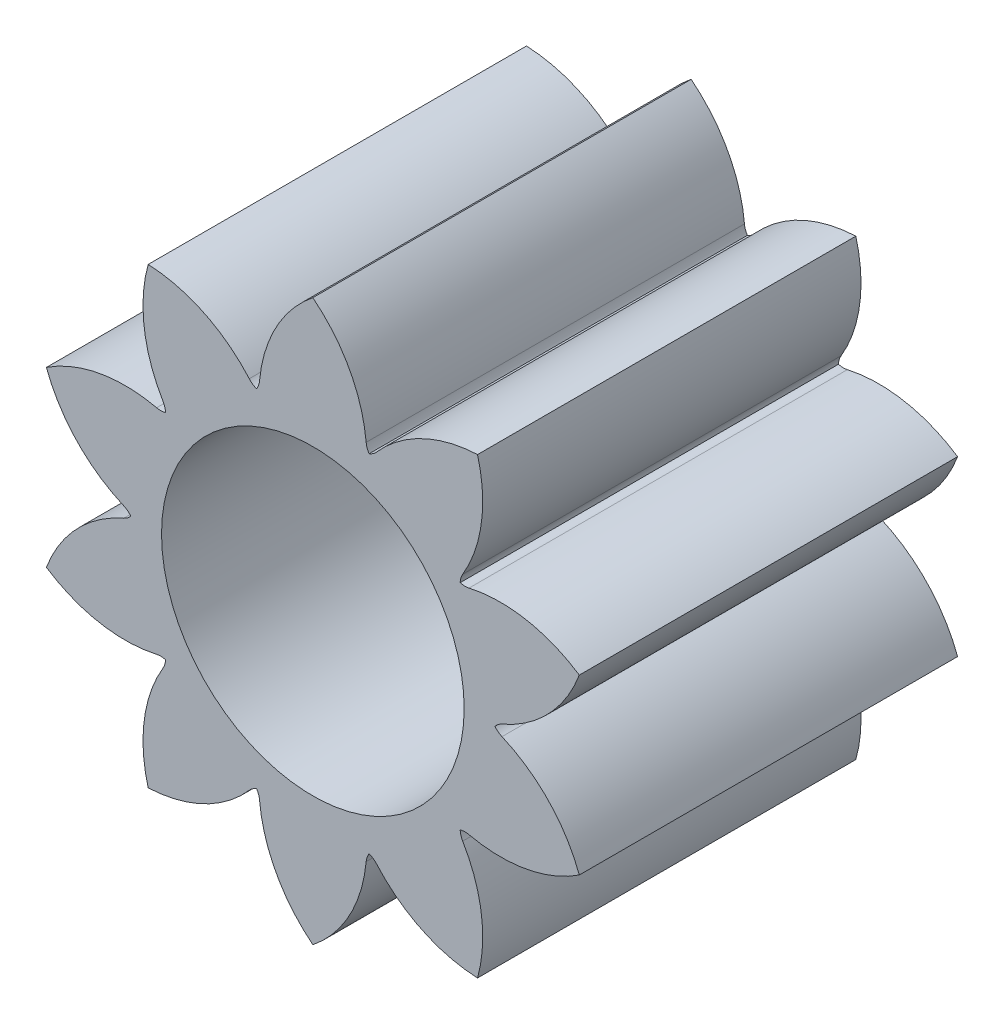
SolidWorks part; units mm, degrees
ref_plane "Front Plane" through (0, 0, 0) normal (0, 0, 1) x (1, 0, 0)
ref_plane "Top Plane" through (0, 0, 0) normal (0, 1, 0) x (1, 0, 0)
ref_plane "Right Plane" through (0, 0, 0) normal (1, 0, 0) x (0, 0, -1)
sketch "Sketch1" plane through (0, 0, 0) normal (0, 0, 1) x (1, 0, 0)
  line L0 (0, 26.4595) -> (0, -24.6987) construction
  line L1 (-24.0319, 0) -> (27.5062, 0) construction
  line L2 (-2.4708, 26.4595) -> (-2.4708, -24.6987) construction
  line L3 (2.4708, 26.4595) -> (2.4708, -24.6987) construction
  line L4 (-2.4708, 15.5347) -> (0, 0) construction
  circle A0 centre (0, 0) radius 18.876 construction
  circle A1 centre (0, 0) radius 15.73 construction
  circle A2 centre (0, 0) radius 12.584 construction
  circle A4 centre (-1.2354, 7.7674) radius 7.865 construction
  arc A5 (0, 18.5145) -> (-3.5225, 11.9979) centre (5.8753, 11.1282) ccw
  arc A6 (3.7185, 11.4445) -> (3.5225, 11.9979) centre (4.7129, 12.1081) cw
  arc A7 (0, 18.5145) -> (3.5225, 11.9979) centre (-5.8753, 11.1282) cw
  arc A8 (-3.7185, 11.4445) -> (-3.5225, 11.9979) centre (-4.7129, 12.1081) ccw
  arc A9 (10.8825, 14.9785) -> (4.2024, 11.777) centre (11.2943, 5.5495) ccw
  arc A10 (9.7353, 7.0731) -> (9.902, 7.636) centre (10.9298, 7.0255) cw
  arc A11 (10.8825, 14.9785) -> (9.902, 7.636) centre (1.7878, 12.4564) cw
  arc A12 (3.7185, 11.4445) -> (4.2024, 11.777) centre (3.3041, 12.5658) ccw
  arc A13 (17.6083, 5.7213) -> (10.3222, 7.0577) centre (12.3992, -2.149) ccw
  arc A14 (12.0334, 0) -> (12.4992, 0.3575) centre (12.9719, -0.7406) cw
  arc A15 (17.6083, 5.7213) -> (12.4992, 0.3575) centre (8.768, 9.0266) cw
  arc A16 (9.7353, 7.0731) -> (10.3222, 7.0577) centre (10.0591, 8.2239) ccw
  arc A17 (17.6083, -5.7213) -> (12.4992, -0.3575) centre (8.768, -9.0266) ccw
  arc A18 (9.7353, -7.0731) -> (10.3222, -7.0577) centre (10.0591, -8.2239) cw
  arc A19 (17.6083, -5.7213) -> (10.3222, -7.0577) centre (12.3992, 2.149) cw
  arc A20 (12.0334, 0) -> (12.4992, -0.3575) centre (12.9719, 0.7406) ccw
  arc A21 (10.8825, -14.9785) -> (9.902, -7.636) centre (1.7878, -12.4564) ccw
  arc A22 (3.7185, -11.4445) -> (4.2024, -11.777) centre (3.3041, -12.5658) cw
  arc A23 (10.8825, -14.9785) -> (4.2024, -11.777) centre (11.2943, -5.5495) cw
  arc A24 (9.7353, -7.0731) -> (9.902, -7.636) centre (10.9298, -7.0255) ccw
  arc A25 (0, -18.5145) -> (3.5225, -11.9979) centre (-5.8753, -11.1282) ccw
  arc A26 (-3.7185, -11.4445) -> (-3.5225, -11.9979) centre (-4.7129, -12.1081) cw
  arc A27 (0, -18.5145) -> (-3.5225, -11.9979) centre (5.8753, -11.1282) cw
  arc A28 (3.7185, -11.4445) -> (3.5225, -11.9979) centre (4.7129, -12.1081) ccw
  arc A29 (-10.8825, -14.9785) -> (-4.2024, -11.777) centre (-11.2943, -5.5495) ccw
  arc A30 (-9.7353, -7.0731) -> (-9.902, -7.636) centre (-10.9298, -7.0255) cw
  arc A31 (-10.8825, -14.9785) -> (-9.902, -7.636) centre (-1.7878, -12.4564) cw
  arc A32 (-3.7185, -11.4445) -> (-4.2024, -11.777) centre (-3.3041, -12.5658) ccw
  arc A33 (-17.6083, -5.7213) -> (-10.3222, -7.0577) centre (-12.3992, 2.149) ccw
  arc A34 (-12.0334, 0) -> (-12.4992, -0.3575) centre (-12.9719, 0.7406) cw
  arc A35 (-17.6083, -5.7213) -> (-12.4992, -0.3575) centre (-8.768, -9.0266) cw
  arc A36 (-9.7353, -7.0731) -> (-10.3222, -7.0577) centre (-10.0591, -8.2239) ccw
  arc A37 (-17.6083, 5.7213) -> (-12.4992, 0.3575) centre (-8.768, 9.0266) ccw
  arc A38 (-9.7353, 7.0731) -> (-10.3222, 7.0577) centre (-10.0591, 8.2239) cw
  arc A39 (-17.6083, 5.7213) -> (-10.3222, 7.0577) centre (-12.3992, -2.149) cw
  arc A40 (-12.0334, 0) -> (-12.4992, 0.3575) centre (-12.9719, -0.7406) ccw
  arc A41 (-10.8825, 14.9785) -> (-9.902, 7.636) centre (-1.7878, 12.4564) ccw
  arc A42 (-3.7185, 11.4445) -> (-4.2024, 11.777) centre (-3.3041, 12.5658) cw
  arc A43 (-10.8825, 14.9785) -> (-4.2024, 11.777) centre (-11.2943, 5.5495) cw
  arc A44 (-9.7353, 7.0731) -> (-9.902, 7.636) centre (-10.9298, 7.0255) ccw
  point P17 (5.8753, 11.1282)
  point P23 (3.5619, 11.2469)
  point P27 (-3.5619, 11.2469)
  point P31 (11.2943, 5.5495)
  point P41 (12.3992, -2.149)
  point P51 (8.768, -9.0266)
  point P61 (1.7878, -12.4564)
  point P71 (-5.8753, -11.1282)
  point P81 (-11.2943, -5.5495)
  point P91 (-12.3992, 2.149)
  point P101 (-8.768, 9.0266)
  point P111 (-1.7878, 12.4564)
  point P120 (0, 0)
  dimension "D1" = 37.752
  dimension "D2" = 31.46
  dimension "D3" = 25.168
  dimension "D7" = 1.1955
  dimension "D5" = 2.4708
  dimension "D6" = 2.4708
  dimension "D8" = 10
extrude "Boss-Extrude1" add sketch "Sketch1" along normal mid plane 25
sketch "Sketch2" plane through (0, 0, 12.5) normal (0, 0, 1) x (1, 0, 0)
  circle A0 centre (0, 0) radius 10
  dimension "D1" = 20
extrude "Cut-Extrude1" cut sketch "Sketch2" against normal through all
